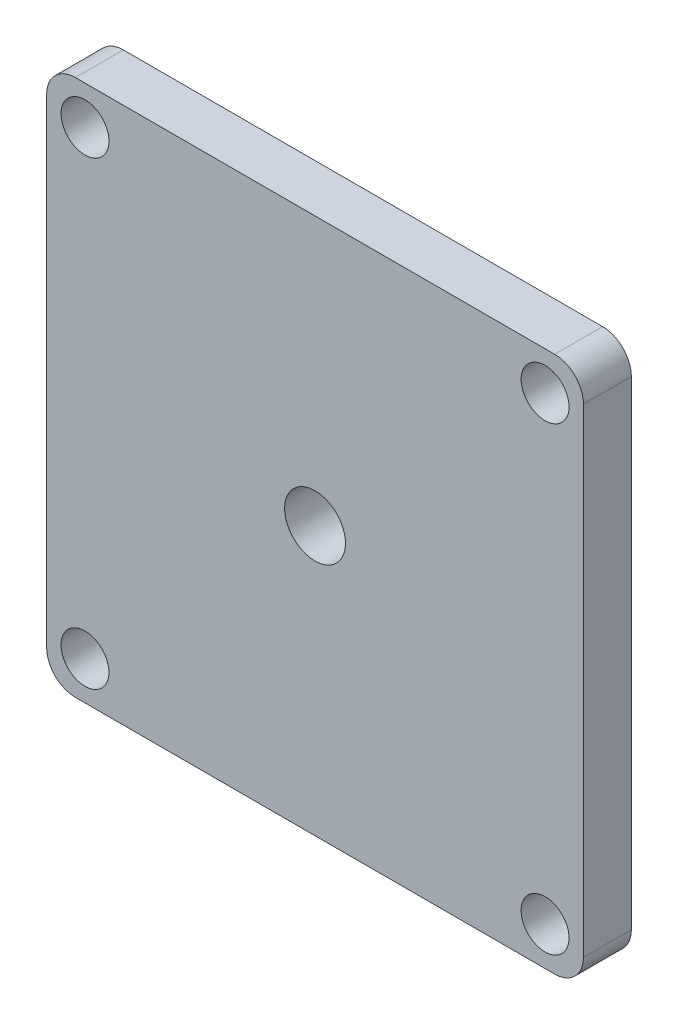
SolidWorks part; units mm, degrees
material "Aluminum Bronze"
ref_plane "Front Plane" through (0, 0, 0) normal (0, 0, 1) x (1, 0, 0)
ref_plane "Top Plane" through (0, 0, 0) normal (0, 1, 0) x (1, 0, 0)
ref_plane "Right Plane" through (0, 0, 0) normal (1, 0, 0) x (0, 0, -1)
sketch "Sketch1" plane through (0, 0, 0) normal (0, 0, 1) x (1, 0, 0)
  line L0 (-28, 25) -> (-28, -25)
  line L1 (-25, -28) -> (25, -28)
  line L2 (28, -25) -> (28, 25)
  line L3 (25, 28) -> (-25, 28)
  arc A0 (-28, -25) -> (-25, -28) centre (-25, -25) ccw
  arc A1 (25, -28) -> (28, -25) centre (25, -25) ccw
  arc A2 (28, 25) -> (25, 28) centre (25, 25) ccw
  arc A3 (-25, 28) -> (-28, 25) centre (-25, 25) ccw
  circle A4 centre (-24, -24) radius 2.5
  circle A5 centre (24, -24) radius 2.5
  circle A6 centre (-24, 24) radius 2.5
  circle A7 centre (0, 0) radius 3.175
  circle A8 centre (24, 24) radius 2.5
  point P22 (0, 0)
extrude "Boss-Extrude1" add sketch "Sketch1" along normal blind 5
